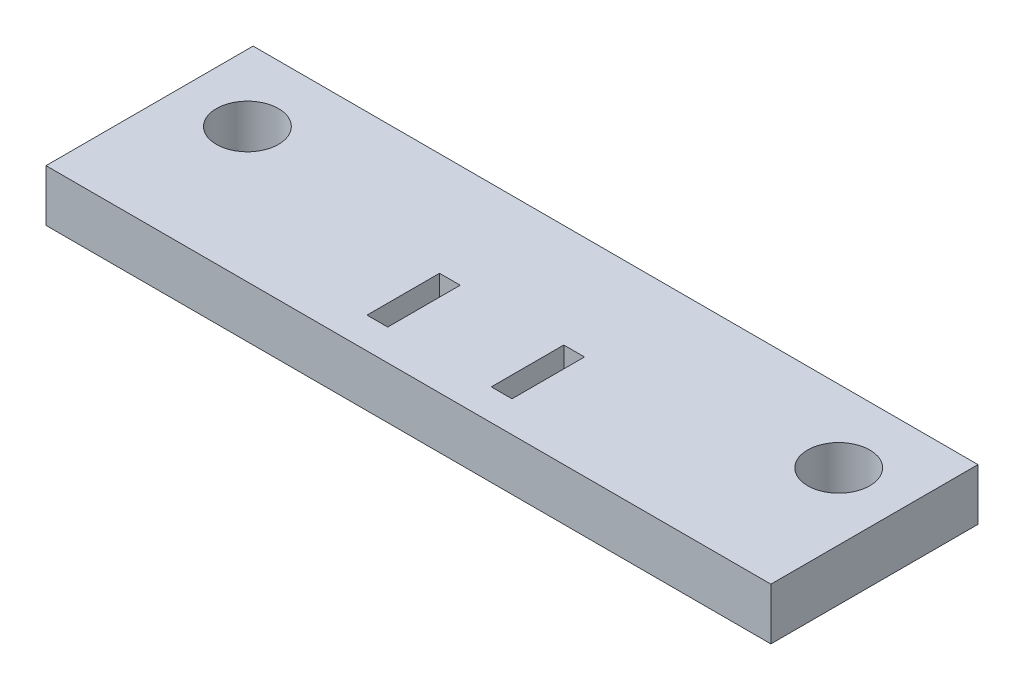
SolidWorks part; units mm, degrees
ref_plane "前视基准面" through (0, 0, 0) normal (0, 0, 1) x (1, 0, 0)
ref_plane "上视基准面" through (0, 0, 0) normal (0, 1, 0) x (1, 0, 0)
ref_plane "右视基准面" through (0, 0, 0) normal (1, 0, 0) x (0, 0, -1)
sketch "草图1" plane through (0, 0, 0) normal (0, 1, 0) x (1, 0, 0)
  line L0 (-47.0349, 3) -> (77.2723, 3) construction
  line L1 (-35, 10) -> (35, 10)
  line L2 (-35, 10) -> (-35, -10)
  line L3 (-35, -10) -> (35, -10)
  line L4 (35, 10) -> (35, -10)
  line L5 (-35, 10) -> (35, -10) construction
  line L6 (-35, -10) -> (35, 10) construction
  line L7 (-28.55, 31.2394) -> (-28.55, -22.6681) construction
  line L8 (28.55, -24.0219) -> (28.55, 31.2394) construction
  line L9 (-6, 21.6836) -> (-6, -18.4505) construction
  line L10 (6, -19.3683) -> (6, 19.3473) construction
  line L11 (-37.5918, -7) -> (42.3554, -7) construction
  line L13 (-7, -7) -> (-5, -7)
  line L14 (-7, -7) -> (-7, 0)
  line L15 (-7, 0) -> (-5, 0)
  line L16 (-5, -7) -> (-5, 0)
  line L17 (5, -7) -> (7, -7)
  line L18 (5, -7) -> (5, 0)
  line L19 (5, 0) -> (7, 0)
  line L20 (7, -7) -> (7, 0)
  circle A0 centre (-28.55, 3) radius 3
  circle A1 centre (28.55, 3) radius 3
  point P0 (0, 0)
  dimension "D5" = 6
  dimension "D6" = 6
  dimension "D1" = 70
  dimension "D2" = 20
  dimension "D3" = 57.1
  dimension "D4" = 28.55
  dimension "D7" = 12
  dimension "D8" = 6
  dimension "D9" = 3
  dimension "D10" = 10
  dimension "D11" = 2
  dimension "D12" = 2
  dimension "D13" = 7
  dimension "D14" = 7
  dimension "D15" = 1
  dimension "D16" = 1
extrude "凸台-拉伸1" add sketch "草图1" along normal blind 5
